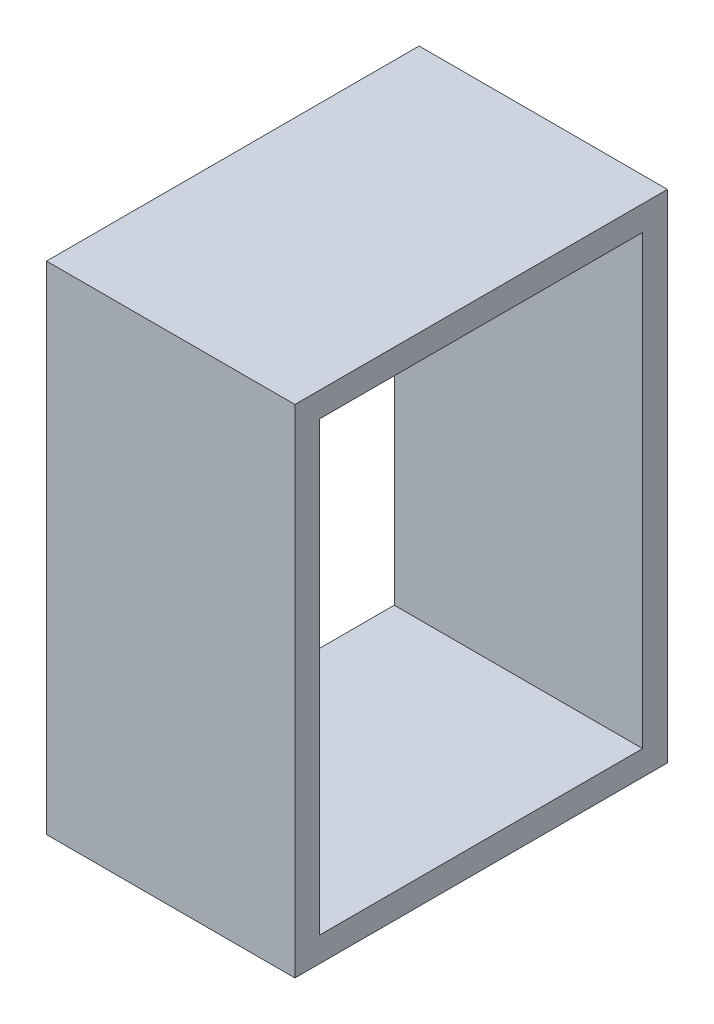
SolidWorks part; units mm, degrees
ref_plane "Спереди" through (0, 0, 0) normal (0, 0, 1) x (1, 0, 0)
ref_plane "Сверху" through (0, 0, 0) normal (0, 1, 0) x (1, 0, 0)
ref_plane "Справа" through (0, 0, 0) normal (1, 0, 0) x (0, 0, -1)
sketch "Эскиз1" plane through (0, 0, 0) normal (1, 0, 0) x (0, 0, -1)
  line L1 (0, 0) -> (150, 0)
  line L2 (0, 0) -> (0, 200)
  line L3 (0, 200) -> (150, 200)
  line L4 (150, 0) -> (150, 200)
  line L5 (10, 10) -> (140, 10)
  line L6 (10, 10) -> (10, 190)
  line L7 (10, 190) -> (140, 190)
  line L8 (140, 10) -> (140, 190)
  dimension "D1" = 200
  dimension "D2" = 150
  dimension "D3" = 180
  dimension "D4" = 130
  dimension "D5" = 10
  dimension "D6" = 10
extrude "Бобышка-Вытянуть1" add sketch "Эскиз1" along normal blind 100
